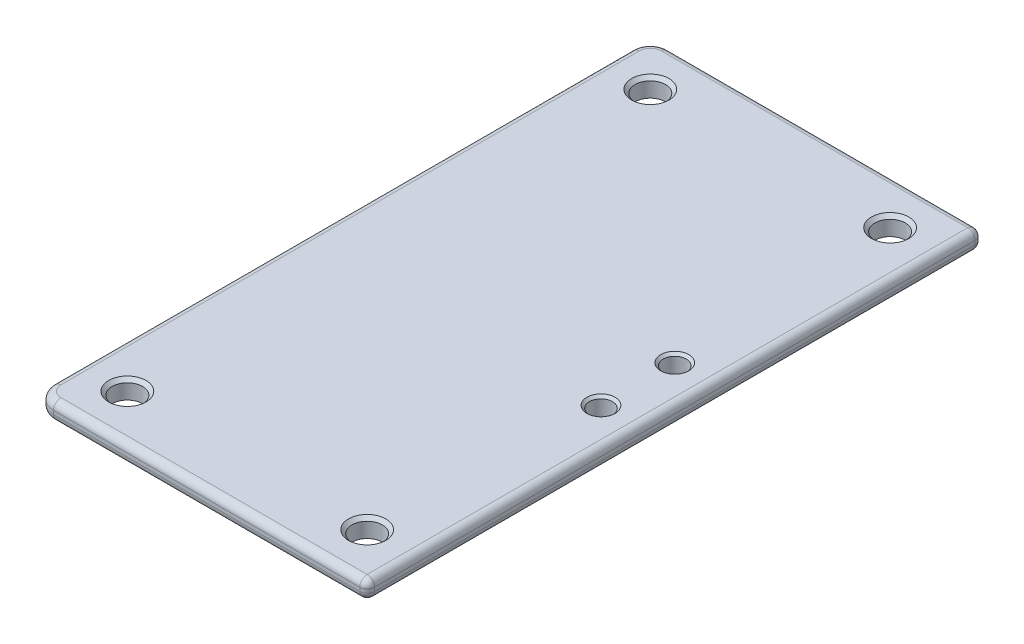
SolidWorks part; units mm, degrees
material "A-玻璃纤维"
ref_plane "前视基准面" through (0, 0, 0) normal (0, 0, 1) x (1, 0, 0)
ref_plane "上视基准面" through (0, 0, 0) normal (0, 1, 0) x (1, 0, 0)
ref_plane "右视基准面" through (0, 0, 0) normal (1, 0, 0) x (0, 0, -1)
sketch "草图1" plane through (0, 0, 0) normal (0, 1, 0) x (1, 0, 0)
  line L1 (-18, -33.35) -> (18, -33.35)
  line L2 (-18, -33.35) -> (-18, 33.35)
  line L3 (-18, 33.35) -> (18, 33.35)
  line L4 (18, -33.35) -> (18, 33.35)
  line L5 (-18, -33.35) -> (18, 33.35) construction
  line L6 (-18, 33.35) -> (18, -33.35) construction
  point P0 (0, 0)
  dimension "D1" = 36
  dimension "D2" = 66.7
extrude "凸台-拉伸1" add sketch "草图1" along normal blind 2 contours L2 L3 L4 L1
sketch "草图2" plane through (0, 2, 0) normal (0, 1, 0) x (1, 0, 0)
  line L0 (-18, 33.35) -> (18, 33.35) construction
  line L1 (-13, -28.35) -> (13, -28.35) construction
  line L2 (-13, -28.35) -> (-13, 28.35) construction
  line L3 (-13, 28.35) -> (13, 28.35) construction
  line L4 (13, -28.35) -> (13, 28.35) construction
  line L5 (-13, -28.35) -> (13, 28.35) construction
  line L6 (-13, 28.35) -> (13, -28.35) construction
  line L7 (18, -33.35) -> (18, 33.35) construction
  point P0 (0, 0)
  point P11 (-13, 28.35)
  point P12 (13, 28.35)
  point P13 (13, -28.35)
  point P14 (-13, -28.35)
  dimension "D1" = 5
  dimension "D2" = 5
hole_wizard "M4 螺纹孔2" positions "草图2" profile "草图4" tap size "M4" standard "GB"
sketch "草图4" plane through (-13, 2, 28.35) normal (1, 0, 0) x (0, 0, 1)
  line L0 (0, 0) -> (0, 2)
  line L1 (0, 2) -> (1.65, 2)
  line L2 (1.65, 2) -> (1.65, 0.375)
  line L3 (1.65, 0.375) -> (2.025, 0)
  line L5 (2.025, 0) -> (0, 0)
  line L6 (-1.65, 0.375) -> (-2.025, 0) construction
  line L11 (0, -6.35) -> (0, 107.95) construction
  dimension "通孔螺纹孔钻头直径" = 3.3
  dimension "通孔螺纹孔钻头深度" = 2
  dimension "近端锥形沉头孔直径" = 4.05
  dimension "近端锥形沉头孔角度" = 90
cosmetic thread "孔螺纹线6" parameters "D2"=4
cosmetic thread "孔螺纹线7" parameters "D2"=4
cosmetic thread "孔螺纹线8" parameters "D2"=4
cosmetic thread "孔螺纹线9" parameters "D2"=4
fillet "圆角1" radius 2 2 edges at (-18, 1, 33.35) (-18, 1, -33.35)
sketch "草图5" plane through (0, 2, 0) normal (0, 1, 0) x (1, 0, 0)
  line L0 (14, 4) -> (14, -4) construction
  line L1 (18, -33.35) -> (18, 33.35) construction
  line L2 (0, 0) -> (34.5778, 0) construction
  point P5 (14, 4)
  point P9 (14, -4)
  dimension "D1" = 8
  dimension "D2" = 4
hole_wizard "M3 螺纹孔1" positions "草图5" profile "草图6" tap size "M3" standard "GB" end condition up to next
sketch "草图6" plane through (14, 2, 4) normal (1, 0, 0) x (0, 0, 1)
  line L0 (0, 0) -> (0, 2)
  line L1 (0, 2) -> (1.25, 2)
  line L2 (1.25, 2) -> (1.25, 0.275)
  line L3 (1.25, 0.275) -> (1.525, 0)
  line L5 (1.525, 0) -> (0, 0)
  line L6 (-1.25, 0.275) -> (-1.525, 0) construction
  line L11 (0, -6.35) -> (0, 107.95) construction
  dimension "通孔螺纹孔钻头直径" = 2.5
  dimension "通孔螺纹孔钻头深度" = 2
  dimension "近端锥形沉头孔直径" = 3.05
  dimension "近端锥形沉头孔角度" = 90
cosmetic thread "孔螺纹线10" parameters "D2"=3
cosmetic thread "孔螺纹线11" parameters "D2"=3
fillet "圆角2" radius 0.8 14 edges at (1, 0, -33.35) (-17.4142, 0, -32.7642) (-18, 0, 0) (-17.4142, 0, 32.7642) (1, 2, -33.35) (-17.4142, 2, -32.7642) (-18, 2, 0) (-17.4142, 2, 32.7642) (1, 0, 33.35) (1, 2, 33.35) (18, 1, 33.35) (18, 2, 0) (18, 1, -33.35) (18, 0, 0)
